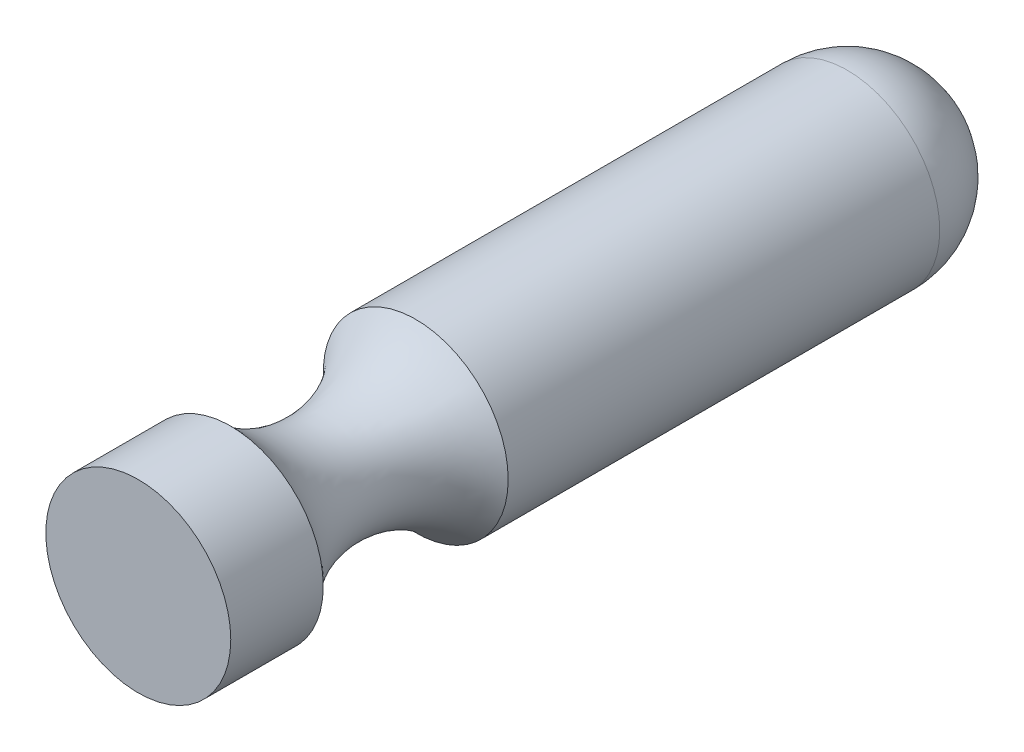
SolidWorks part; units mm, degrees
ref_plane "Front Plane" through (0, 0, 0) normal (0, 0, 1) x (1, 0, 0)
ref_plane "Top Plane" through (0, 0, 0) normal (0, 1, 0) x (1, 0, 0)
ref_plane "Right Plane" through (0, 0, 0) normal (1, 0, 0) x (0, 0, -1)
sketch "Sketch1" plane through (0, 0, 0) normal (0, 1, 0) x (1, 0, 0)
  line L0 (0, 0) -> (19.05, 0)
  line L1 (19.05, 0) -> (19.05, 19.05)
  line L2 (19.05, 57.15) -> (19.05, 146.05)
  line L3 (0, 0) -> (0, 165.1)
  arc A0 (19.05, 19.05) -> (19.05, 57.15) centre (35.8505, 38.1) cw
  arc A1 (19.05, 146.05) -> (0, 165.1) centre (0, 146.05) ccw
  dimension "D3" = 19.05
  dimension "D5" = 25.4
  dimension "D1" = 19.05
  dimension "D2" = 19.05
  dimension "D4" = 165.1
  dimension "D6" = 38.1
revolve "Revolve1" add sketch "Sketch1" angle 360 about L3
ref_plane "Plane2" through (0, 0, 0) normal (0, 0, 1) x (1, 0, 0)
